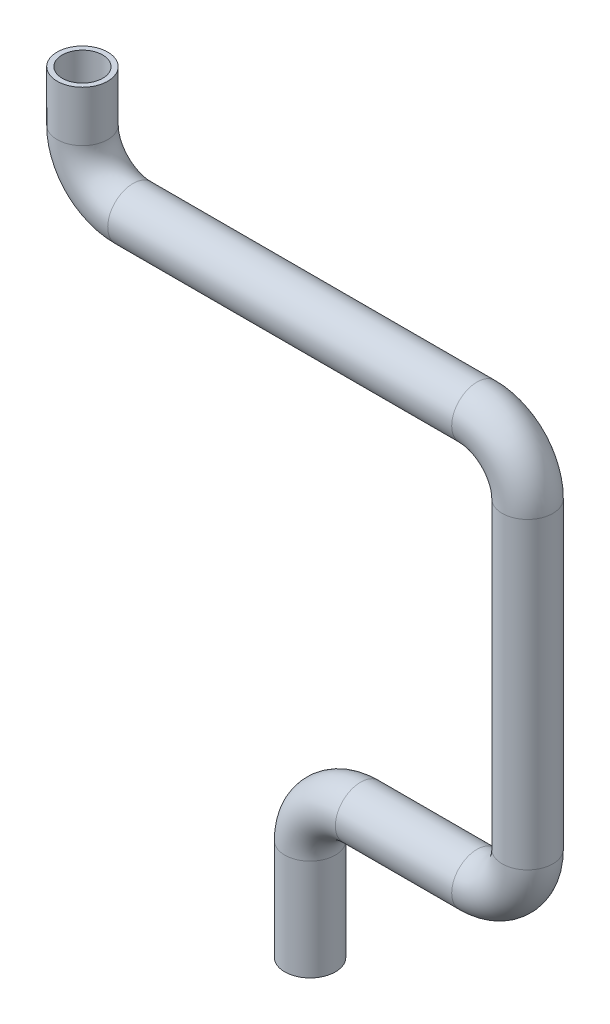
SolidWorks part; units mm, degrees
ref_plane "前视基准面" through (0, 0, 0) normal (0, 0, 1) x (1, 0, 0)
ref_plane "上视基准面" through (0, 0, 0) normal (0, 1, 0) x (1, 0, 0)
ref_plane "右视基准面" through (0, 0, 0) normal (1, 0, 0) x (0, 0, -1)
other "Configuration Table"
sketch "草图1" plane through (0, 0, 0) normal (0, 0, 1) x (1, 0, 0)
  line L0 (0, 0) -> (0, 20) construction
  line L1 (-10, 30) -> (-33, 30) construction
  line L2 (-43, 40) -> (-43, 100) construction
  line L3 (0, -1000) -> (0, 49000) construction
  line L4 (43, 40) -> (43, 100)
  line L5 (10, 30) -> (33, 30)
  line L6 (0, 0) -> (0, 20)
  line L7 (33, 110) -> (-35, 110)
  line L8 (-45, 120) -> (-45, 130)
  arc A0 (0, 20) -> (-10, 30) centre (-10, 20) ccw construction
  arc A1 (-33, 30) -> (-43, 40) centre (-33, 40) cw construction
  arc A2 (33, 30) -> (43, 40) centre (33, 40) ccw
  arc A3 (0, 20) -> (10, 30) centre (10, 20) cw
  arc A4 (43, 100) -> (33, 110) centre (33, 100) ccw
  arc A5 (-35, 110) -> (-45, 120) centre (-35, 120) cw
  point P7 (0, 30)
  point P10 (-43, 30)
  point P19 (43, 30)
  point P23 (43, 100)
  point P24 (43, 110)
  point P28 (-45, 110)
  dimension "D4" = 10
  dimension "D6" = 88
  dimension "D7" = 10
  dimension "D9" = 10
  dimension "D1" = 43
  dimension "D2" = 30
  dimension "D3" = 70
  dimension "D5" = 70
  dimension "D8" = 20
sweep "扫描1" add path "草图1" circular profile diameter 10 parameters "D3"=10
sketch "草图7" plane through (0, 0, 0) normal (0, 0, 1) x (1, 0, 0)
  line L0 (0, 0) -> (0, 20) construction
  line L1 (-10, 30) -> (-33, 30) construction
  line L2 (-43, 40) -> (-43, 100) construction
  line L3 (0, 0) -> (0, 20)
  line L4 (-10, 30) -> (-33, 30) construction
  line L5 (-43, 40) -> (-43, 100) construction
  line L6 (43, 40) -> (43, 100)
  line L7 (10, 30) -> (33, 30)
  line L8 (33, 110) -> (-35, 110) construction
  line L10 (33, 110) -> (-35, 110)
  line L11 (-45, 120) -> (-45, 130)
  line L12 (-40, 130) -> (-50, 130) construction
  arc A0 (0, 20) -> (-10, 30) centre (-10, 20) ccw construction
  arc A1 (-43, 40) -> (-33, 30) centre (-33, 40) ccw construction
  arc A2 (0, 20) -> (-10, 30) centre (-10, 20) ccw construction
  arc A3 (-43, 40) -> (-33, 30) centre (-33, 40) ccw construction
  arc A4 (43, 40) -> (33, 30) centre (33, 40) cw
  arc A5 (0, 20) -> (10, 30) centre (10, 20) cw
  arc A6 (43, 100) -> (33, 110) centre (33, 100) ccw construction
  arc A7 (43, 100) -> (33, 110) centre (33, 100) ccw
  arc A8 (-35, 110) -> (-45, 120) centre (-35, 120) cw
  point P19 (43, 100)
  dimension "D1" = 10
sweep "切除-扫描1" cut path "草图7" circular profile diameter 8 parameters "D3"=8
ref_plane "基准面1" through (43, 0, 0) normal (1, 0, 0) x (0, 0, -1)
sketch "草图18" plane through (43, 0, 0) normal (1, 0, 0) x (0, 0, -1)
  line L0 (0, -970) -> (0, 49030) construction
  line L1 (10, 140) -> (80, 140) construction
  line L2 (90, 150) -> (90, 160) construction
  line L3 (4, 130) -> (-4, 130) construction
  line L4 (0, 30) -> (0, 130) construction
  line L5 (-90, 150) -> (-90, 160)
  line L6 (-10, 140) -> (-80, 140)
  arc A0 (80, 140) -> (90, 150) centre (80, 150) ccw construction
  arc A1 (10, 140) -> (0, 130) centre (10, 130) ccw construction
  arc A2 (-10, 140) -> (0, 130) centre (-10, 130) cw
  arc A3 (-80, 140) -> (-90, 150) centre (-80, 150) cw
  point P7 (0, 90.626)
  point P8 (90, 140)
  point P11 (90, 90.626)
  point P14 (0, 140)
  point P15 (90, 90.626)
  point P18 (0, 90.626)
  point P27 (-90, 90.626)
  point P28 (-90, 140)
  dimension "D3" = 10
  dimension "D4" = 90
  dimension "D5" = 10
  dimension "D6" = 10
  dimension "D1" = 90
  dimension "D2" = 20
sketch "草图23" plane through (43, 0, 0) normal (1, 0, 0) x (0, 0, -1)
  line L0 (0, -1000) -> (0, 49000) construction
  line L1 (90, 150) -> (90, 160) construction
  line L2 (-10, 140) -> (-80, 140)
  line L3 (10, 140) -> (80, 140) construction
  line L4 (90, 150) -> (90, 160) construction
  line L5 (10, 140) -> (80, 140) construction
  line L6 (-90, 150) -> (-90, 160)
  arc A0 (-10, 140) -> (0, 130) centre (-10, 130) cw
  arc A1 (80, 140) -> (90, 150) centre (80, 150) ccw construction
  arc A2 (-80, 140) -> (-90, 150) centre (-80, 150) cw
  arc A3 (10, 140) -> (0, 130) centre (10, 130) ccw construction
  arc A4 (80, 140) -> (90, 150) centre (80, 150) ccw construction
  arc A5 (10, 140) -> (0, 130) centre (10, 130) ccw construction
